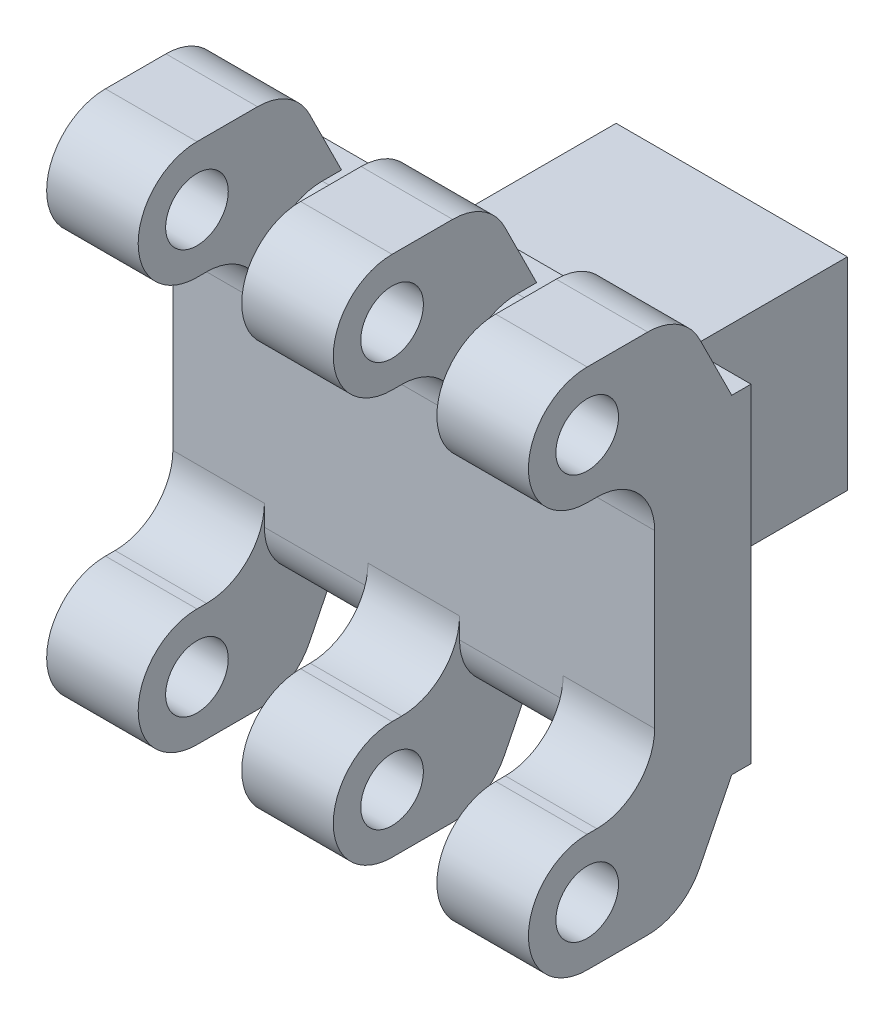
SolidWorks part; units mm, degrees
ref_plane "Front Plane" through (0, 0, 0) normal (0, 0, 1) x (1, 0, 0)
ref_plane "Top Plane" through (0, 0, 0) normal (0, 1, 0) x (1, 0, 0)
ref_plane "Right Plane" through (0, 0, 0) normal (1, 0, 0) x (0, 0, -1)
sketch "Sketch1" plane through (0, 0, 0) normal (0, 0, 1) x (1, 0, 0)
  line L1 (-25, -17.055) -> (25, -17.055)
  line L2 (-25, -17.055) -> (-25, 17.055)
  line L3 (-25, 17.055) -> (25, 17.055)
  line L4 (25, -17.055) -> (25, 17.055)
  line L5 (-25, -17.055) -> (25, 17.055) construction
  line L6 (-25, 17.055) -> (25, -17.055) construction
  point P0 (0, 0)
  dimension "D1" = 50
  dimension "D2" = 34.11
extrude "Boss-Extrude1" add sketch "Sketch1" along normal blind 10
sketch "Sketch3" plane through (0, 0, 0) normal (0, 0, -1) x (-1, 0, 0)
  line L1 (-20.5, -10.5) -> (20.5, -10.5)
  line L2 (-20.5, -10.5) -> (-20.5, 10.5)
  line L3 (-20.5, 10.5) -> (20.5, 10.5)
  line L4 (20.5, -10.5) -> (20.5, 10.5)
  line L5 (-20.5, -10.5) -> (20.5, 10.5) construction
  line L6 (-20.5, 10.5) -> (20.5, -10.5) construction
  point P0 (0, 0)
  dimension "D1" = 41
  dimension "D2" = 21
extrude "Boss-Extrude2" add sketch "Sketch3" along normal blind 3
sketch "Sketch2" plane through (0, 0, 0) normal (0, 0, -1) x (-1, 0, 0)
  line L0 (0, 0) -> (0, -4.7855) construction
  line L1 (-16, -15.5) -> (-12.5, -15.5)
  line L2 (-16, -15.5) -> (-16, 15.5)
  line L3 (-16, 15.5) -> (-12.5, 15.5)
  line L4 (-12.5, -15.5) -> (-12.5, 15.5)
  line L5 (-16, -15.5) -> (-12.5, 15.5) construction
  line L6 (-16, 15.5) -> (-12.5, -15.5) construction
  line L7 (16, 15.5) -> (12.5, 15.5)
  line L8 (12.5, -15.5) -> (12.5, 15.5)
  line L9 (16, -15.5) -> (12.5, -15.5)
  line L10 (16, -15.5) -> (16, 15.5)
  point P0 (-14.25, 0)
  dimension "D1" = 12.5
  dimension "D2" = 3.5
  dimension "D3" = 31
extrude "Cut-Extrude1" cut sketch "Sketch2" against normal blind 7 and the other way through all
sketch "Sketch4" plane through (0, 0, -3) normal (0, 0, -1) x (-1, 0, 0)
  line L0 (12.5, 15.5) -> (12.5, -15.5) construction
  line L1 (-12.5, -10.5) -> (12.5, -10.5)
  line L2 (-12.5, -10.5) -> (-12.5, 10.5)
  line L3 (-12.5, 10.5) -> (12.5, 10.5)
  line L4 (12.5, -10.5) -> (12.5, 10.5)
  line L5 (-12.5, -10.5) -> (12.5, 10.5) construction
  line L6 (-12.5, 10.5) -> (12.5, -10.5) construction
  line L7 (12.5, 10.5) -> (12.5, 15.5) construction
  point P0 (0, 0)
extrude "Boss-Extrude3" add sketch "Sketch4" along normal blind 20
sketch "Sketch5" plane through (0, 0, -23) normal (0, 0, -1) x (-1, 0, 0)
  circle A0 centre (0, 0) radius 8.6
  dimension "D1" = 17.2
extrude "Cut-Extrude2" cut sketch "Sketch5" against normal up to surface (30 mm away) up to face at (-14.25, 0, 7)
sketch "Sketch6" plane through (25, 0, 0) normal (1, 0, 0) x (0, 0, -1)
  line L0 (0, 27.5) -> (0, -27.5) construction
  line L1 (24.805, 0) -> (-24.805, 0) construction
  line L2 (-17, 27.1) -> (-7, 27.1)
  line L3 (-7, 27.1) -> (-2, 17.055)
  line L4 (-10, 17.055) -> (0, 17.055) construction
  line L5 (-17, 14.9) -> (-10, 14.9)
  line L6 (-10, -17.055) -> (-10, 17.055) construction
  line L7 (-10, 14.9) -> (-10, 17.055)
  line L8 (-10, 17.055) -> (-2, 17.055)
  arc A0 (-17, 27.1) -> (-17, 14.9) centre (-17, 21) ccw
  circle A1 centre (-17, 21) radius 3.25
  arc A2 (-17, 14.9) -> (-17, 27.1) centre (-17, 21) ccw construction
  dimension "D1" = 6.5
  dimension "D2" = 12.2
  dimension "D3" = 17
  dimension "D4" = 21
  dimension "D5" = 10
  dimension "D6" = 2
extrude "Boss-Extrude4" add sketch "Sketch6" against normal blind 9.5
pattern_linear "LPattern1" count 3 spacing 20.25 along (-1, 0, 0) of "Boss-Extrude4"
mirror "Mirror1" about plane through (0, 0, 0) normal (0, 1, 0) of "LPattern1", "Boss-Extrude4"
fillet "Fillet1" radius 6 12 edges at (20.25, -27.1, 7) (0, -27.1, 7) (-20.25, -27.1, 7) (20.25, 27.1, 7) (0, 27.1, 7) (-20.25, 27.1, 7) (-20.25, -14.9, 10) (0, -14.9, 10) (20.25, -14.9, 10) (20.25, 14.9, 10) (0, 14.9, 10) (-20.25, 14.9, 10)
sketch "Sketch7" plane through (12.5, 0, 0) normal (1, 0, 0) x (0, 0, -1)
  line L0 (0, 27.5) -> (0, -27.5) construction
  line L1 (23, 10.5) -> (0, 10.5)
  line L2 (23, 10.5) -> (23, -10.5)
  line L3 (23, -10.5) -> (0, -10.5)
  line L4 (0, 10.5) -> (0, -10.5)
  line L5 (3, -10.5) -> (0, -10.5) construction
extrude "Cut-Extrude3" cut sketch "Sketch7" against normal blind 0.5 contours L2 L1 L4 L3
mirror "Mirror2" about plane through (0, 0, 0) normal (1, 0, 0) of "Cut-Extrude3"
fillet "Fillet2" radius 6 4 edges at (10.125, -17.055, 10) (-10.125, -17.055, 10) (-10.125, 17.055, 10) (10.125, 17.055, 10)
